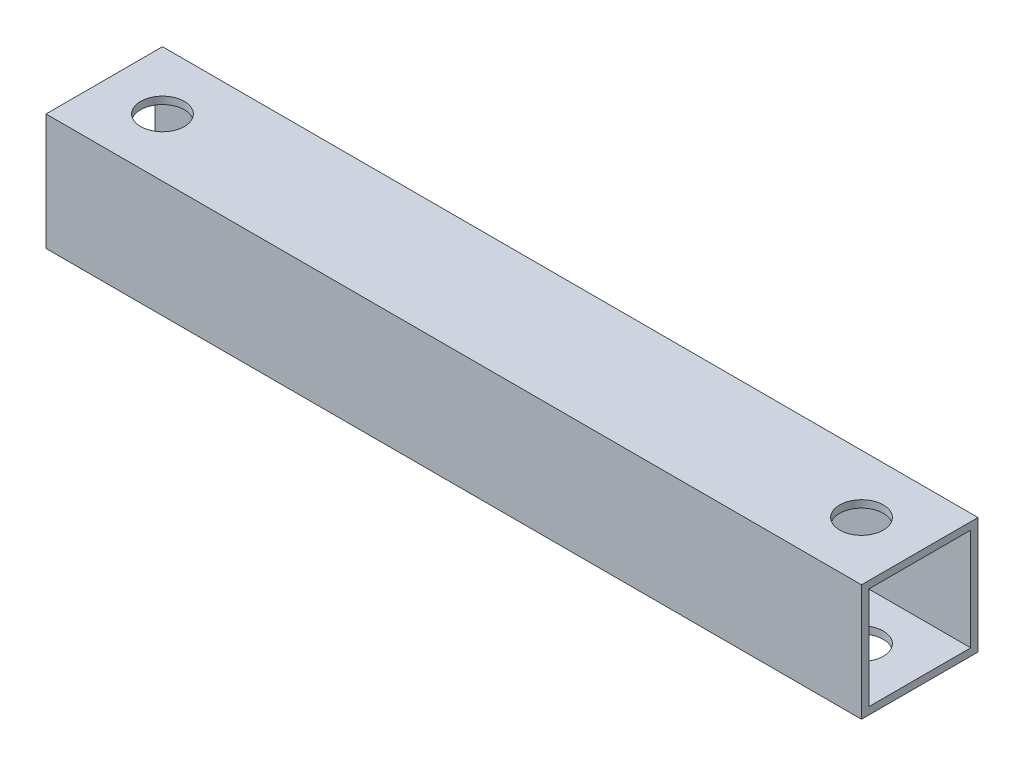
SolidWorks part; units mm, degrees
ref_plane "Front Plane" through (0, 0, 0) normal (0, 0, 1) x (1, 0, 0)
ref_plane "Top Plane" through (0, 0, 0) normal (0, 1, 0) x (1, 0, 0)
ref_plane "Right Plane" through (0, 0, 0) normal (1, 0, 0) x (0, 0, -1)
sketch "Sketch1" plane through (0, 0, 0) normal (1, 0, 0) x (0, 0, -1)
  line L1 (-11.1125, -11.1125) -> (11.1125, -11.1125)
  line L2 (-11.1125, -11.1125) -> (-11.1125, 11.1125)
  line L3 (-11.1125, 11.1125) -> (11.1125, 11.1125)
  line L4 (11.1125, -11.1125) -> (11.1125, 11.1125)
  line L5 (-11.1125, -11.1125) -> (11.1125, 11.1125) construction
  line L6 (-11.1125, 11.1125) -> (11.1125, -11.1125) construction
  line L7 (-12.7, -12.7) -> (12.7, -12.7)
  line L8 (-12.7, -12.7) -> (-12.7, 12.7)
  line L9 (-12.7, 12.7) -> (12.7, 12.7)
  line L10 (12.7, -12.7) -> (12.7, 12.7)
  line L11 (-12.7, -12.7) -> (12.7, 12.7) construction
  line L12 (-12.7, 12.7) -> (12.7, -12.7) construction
  point P0 (0, 0)
  point P6 (0, 0)
  dimension "D1" = 25.4
  dimension "D2" = 1.5875
extrude "Boss-Extrude1" add sketch "Sketch1" along normal blind 177.8
sketch "Sketch2" plane through (0, 12.7, 0) normal (0, 1, 0) x (1, 0, 0)
  line L0 (0, 0) -> (12.7, 0) construction
  line L1 (12.7, 0) -> (165.1, 0) construction
  line L2 (165.1, 0) -> (177.8, 0) construction
  line L3 (177.8, 12.7) -> (177.8, -12.7) construction
  circle A0 centre (12.7, 0) radius 4.7625
  circle A1 centre (165.1, 0) radius 4.7625
  dimension "D2" = 9.525
  dimension "D1" = 152.4
extrude "Cut-Extrude1" cut sketch "Sketch2" against normal through all
